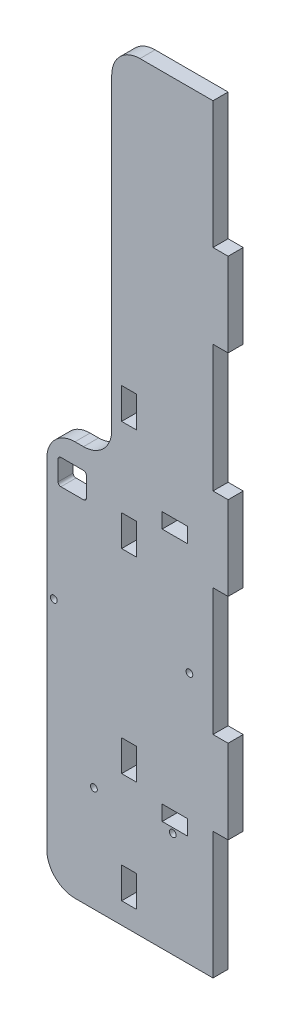
SolidWorks part; units mm, degrees
ref_plane "Front Plane" through (0, 0, 0) normal (0, 0, 1) x (1, 0, 0)
ref_plane "Top Plane" through (0, 0, 0) normal (0, 1, 0) x (1, 0, 0)
ref_plane "Right Plane" through (0, 0, 0) normal (1, 0, 0) x (0, 0, -1)
sketch "Model" plane through (0, 0, 0) normal (0, 0, 1) x (1, 0, 0)
  line L655 (31.85, 154.5) -> (26.5, 154.5)
  line L656 (31.85, 165.5) -> (31.85, 154.5)
  line L657 (26.5, 165.5) -> (31.85, 165.5)
  line L658 (26.5, 154.5) -> (26.5, 165.5)
  line L659 (49.85, 134) -> (49.85, 128.65)
  line L660 (40.85, 134) -> (49.85, 134)
  line L661 (40.85, 128.65) -> (40.85, 134)
  line L662 (49.85, 128.65) -> (40.85, 128.65)
  line L663 (31.85, 115.5) -> (26.5, 115.5)
  line L664 (31.85, 126.5) -> (31.85, 115.5)
  line L665 (26.5, 126.5) -> (31.85, 126.5)
  line L666 (26.5, 115.5) -> (26.5, 126.5)
  line L667 (49.85, 44.35) -> (49.85, 39)
  line L668 (40.85, 44.35) -> (49.85, 44.35)
  line L669 (40.85, 39) -> (40.85, 44.35)
  line L670 (49.85, 39) -> (40.85, 39)
  line L671 (26.5, 57.5) -> (31.85, 57.5)
  line L672 (26.5, 46.5) -> (26.5, 57.5)
  line L673 (31.85, 46.5) -> (26.5, 46.5)
  line L674 (31.85, 57.5) -> (31.85, 46.5)
  line L675 (26.5, 18.5) -> (31.85, 18.5)
  line L676 (26.5, 7.5) -> (26.5, 18.5)
  line L677 (31.85, 7.5) -> (26.5, 7.5)
  line L678 (31.85, 18.5) -> (31.85, 7.5)
  line L679 (5, 123.7119) -> (13, 123.7119)
  line L680 (14, 124.7119) -> (14, 131.7119)
  line L681 (13, 132.7119) -> (5, 132.7119)
  line L682 (4, 131.7119) -> (4, 124.7119)
  line L683 (58.85, 269) -> (33, 269)
  line L684 (58.85, 224) -> (58.85, 269)
  line L685 (64.2, 224) -> (58.85, 224)
  line L686 (64.2, 194.3333) -> (64.2, 224)
  line L687 (58.85, 194.3333) -> (64.2, 194.3333)
  line L688 (58.85, 149.3333) -> (58.85, 194.3333)
  line L689 (64.2, 149.3333) -> (58.85, 149.3333)
  line L690 (64.2, 119.6667) -> (64.2, 149.3333)
  line L691 (58.85, 119.6667) -> (64.2, 119.6667)
  line L692 (58.85, 74.6667) -> (58.85, 119.6667)
  line L693 (64.2, 74.6667) -> (58.85, 74.6667)
  line L694 (64.2, 45) -> (64.2, 74.6667)
  line L695 (58.85, 45) -> (64.2, 45)
  line L696 (58.85, 0) -> (58.85, 45)
  line L697 (10, 0) -> (58.85, 0)
  line L698 (0, 130) -> (0, 10)
  line L699 (13, 140) -> (10, 140)
  line L700 (23, 259) -> (23, 150)
  arc A165 (10, 140) -> (0, 130) centre (10, 130) ccw
  arc A166 (13, 140) -> (23, 150) centre (13, 150) ccw
  arc A167 (33, 269) -> (23, 259) centre (33, 259) ccw
  arc A168 (0, 10) -> (10, 0) centre (10, 10) ccw
  circle A169 centre (2.5, 88.0279) radius 1.2
  circle A170 centre (44.6, 37.2279) radius 1.2
  circle A171 centre (16.7, 37.2279) radius 1.2
  circle A172 centre (50.5, 89.3279) radius 1.2
  arc A173 (4, 124.7119) -> (5, 123.7119) centre (5, 124.7119) ccw
  arc A174 (13, 123.7119) -> (14, 124.7119) centre (13, 124.7119) ccw
  arc A175 (14, 131.7119) -> (13, 132.7119) centre (13, 131.7119) ccw
  arc A176 (5, 132.7119) -> (4, 131.7119) centre (5, 131.7119) ccw
extrude "Boss-Extrude1" add sketch "Model" along normal blind 5.35
